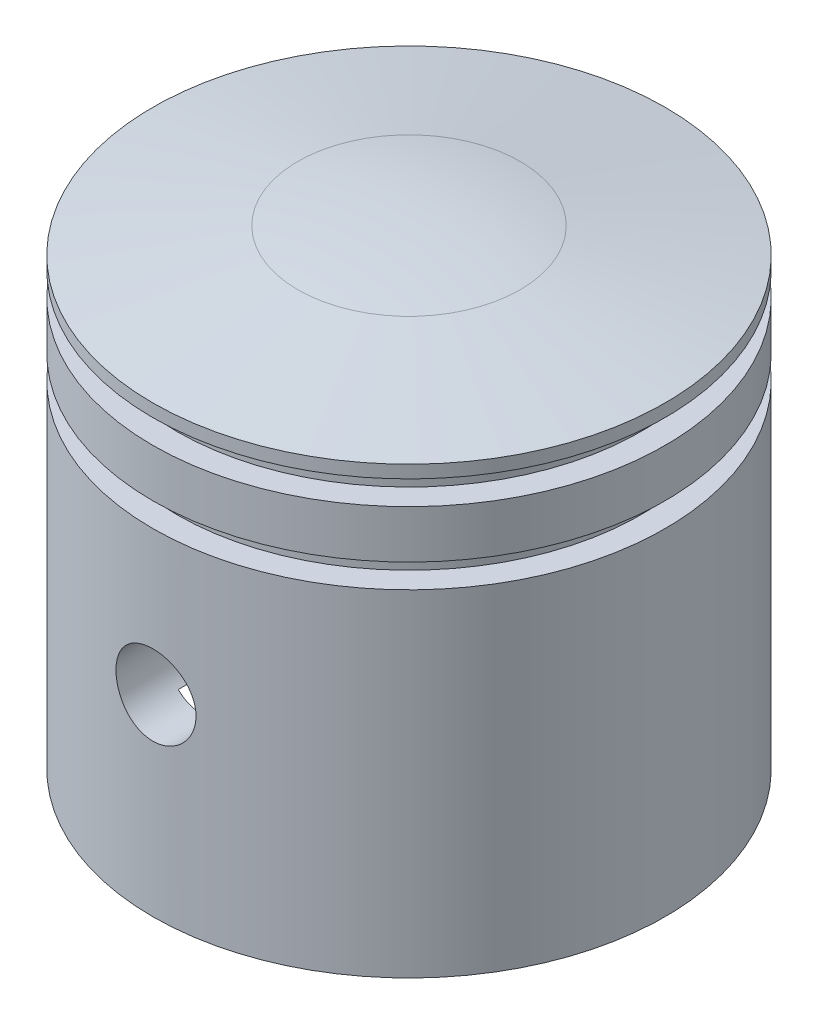
SolidWorks part; units mm, degrees
material "AISI Type 316L stainless steel"
ref_plane "Front Plane" through (0, 0, 0) normal (0, 0, 1) x (1, 0, 0)
ref_plane "Top Plane" through (0, 0, 0) normal (0, 1, 0) x (1, 0, 0)
ref_plane "Right Plane" through (0, 0, 0) normal (1, 0, 0) x (0, 0, -1)
sketch "Sketch1" plane through (0, 0, 0) normal (0, 0, 1) x (1, 0, 0)
  line L0 (0, 0) -> (16, 0)
  line L1 (16, 0) -> (16, 27.7958)
  line L2 (16, 27.7958) -> (6.9459, 29.3923)
  line L3 (0, 30) -> (0, 0)
  line L4 (0, 30) -> (38.5859, 30) construction
  arc A0 (6.9459, 29.3923) -> (0, 30) centre (0, -10) ccw
  point P8 (38.5859, 29.7279)
  point P9 (0, 0)
  point P10 (0, -10)
  point P11 (0, -10)
  dimension "D3" = 40
  dimension "D1" = 30
  dimension "D2" = 16
  dimension "D4" = 10
revolve "Revolve1" add sketch "Sketch1" angle 360 about L3
sketch "Sketch2" plane through (0, 0, 0) normal (0, 0, 1) x (1, 0, 0)
  line L0 (0, 34.0055) -> (0, -7.0594) construction
  line L1 (-16, 0) -> (16, 0) construction
  line L2 (14.5, 27) -> (16, 27)
  line L3 (14.5, 27) -> (14.5, 25.5)
  line L4 (14.5, 25.5) -> (16, 25.5)
  line L5 (16, 27) -> (16, 25.5)
  line L6 (14.5, 22.5) -> (16, 22.5)
  line L7 (14.5, 22.5) -> (14.5, 21)
  line L8 (14.5, 21) -> (16, 21)
  line L9 (16, 22.5) -> (16, 21)
  dimension "D1" = 3
  dimension "D2" = 1.5
  dimension "D3" = 21
  dimension "D4" = 14.5
revolve "Cut-Revolve1" cut sketch "Sketch2" angle 360 about L0
sketch "Sketch3" plane through (0, 0, 0) normal (0, 0, 1) x (1, 0, 0)
  circle A0 centre (0, 12) radius 2.5
  dimension "D1" = 5
  dimension "D2" = 12
extrude "Cut-Extrude1" cut sketch "Sketch3" against normal through all and the other way through all
sketch "Sketch4" plane through (0, 0, 0) normal (0, -1, 0) x (1, 0, 0)
  circle A0 centre (0, 0) radius 10
  dimension "D1" = 20
extrude "Cut-Extrude2" cut sketch "Sketch4" against normal blind 24
sketch "Sketch5" plane through (0, 0, 0) normal (0, -1, 0) x (1, 0, 0)
  circle A0 centre (0, 0) radius 13
  dimension "D1" = 26
extrude "Cut-Extrude3" cut sketch "Sketch5" against normal blind 10
